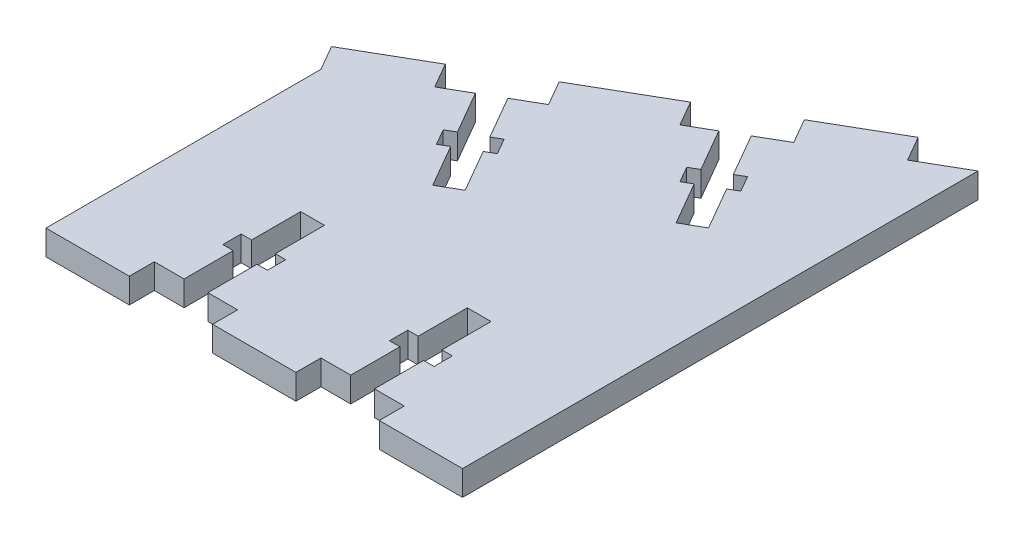
SolidWorks part; units mm, degrees
ref_plane "Front Plane" through (0, 0, 0) normal (0, 0, 1) x (1, 0, 0)
ref_plane "Top Plane" through (0, 0, 0) normal (0, 1, 0) x (1, 0, 0)
ref_plane "Right Plane" through (0, 0, 0) normal (1, 0, 0) x (0, 0, -1)
sketch "Sketch1" plane through (0, 0, 0) normal (0, 1, 0) x (1, 0, 0)
  line L0 (0, 0) -> (50, 0)
  line L1 (50, 0) -> (50, 28.8675)
  line L2 (50, 28.8675) -> (0, 0)
  line L3 (0, 0) -> (-1.7321, 3)
  line L4 (0, 0) -> (50, 0)
  line L5 (0, 0) -> (0, -30)
  line L6 (0, -30) -> (50, -30)
  line L7 (50, 0) -> (50, -30)
  line L8 (0, -30) -> (10, -30)
  line L9 (0, -30) -> (0, -33)
  line L10 (0, -33) -> (10, -33)
  line L11 (10, -30) -> (10, -33)
  line L12 (20, -30) -> (30, -30)
  line L13 (20, -30) -> (20, -33)
  line L14 (20, -33) -> (30, -33)
  line L15 (30, -30) -> (30, -33)
  line L16 (40, -30) -> (50, -30)
  line L17 (40, -30) -> (40, -33)
  line L18 (40, -33) -> (50, -33)
  line L19 (50, -30) -> (50, -33)
  line L20 (-1.7321, 3) -> (6.9282, 8)
  line L21 (6.9282, 8) -> (8.6603, 5)
  line L22 (17.3205, 10) -> (15.5885, 13)
  line L23 (15.5885, 13) -> (25.5885, 18.7735)
  line L24 (25.5885, 18.7735) -> (27.3205, 15.7735)
  line L25 (27.3205, 15.7735) -> (17.3205, 10)
  line L26 (8.6603, 5) -> (0, 0)
  line L27 (35.9808, 20.7735) -> (34.2487, 23.7735)
  line L28 (34.2487, 23.7735) -> (42.909, 28.7735)
  line L29 (42.909, 28.7735) -> (44.641, 25.7735)
  dimension "D1" = 0
  dimension "D2" = 30
  dimension "D3" = 10
  dimension "D4" = 10
  dimension "D5" = 10
  dimension "D6" = 10
  dimension "D7" = 3
  dimension "D8" = 3
  dimension "D9" = 3
  dimension "D10" = 30
  dimension "D11" = 3
  dimension "D12" = 3
  dimension "D13" = 3
  dimension "D14" = 10
  dimension "D15" = 10
  dimension "D16" = 10
  dimension "D17" = 10
  dimension "D18" = 10
extrude "Boss-Extrude1" add sketch "Sketch1" along normal blind 3 contours L1 L2 L0 | L21 L20 L3 L2 | L7 L0 L5 L6 | L11 L6 L9 L10 | L15 L6 L13 L14 | L19 L6 L17 L18 | L24 L23 L22 L2 | L29 L28 L27 L2
sketch "Sketch2" plane through (0, 3, 0) normal (0, 1, 0) x (1, 0, 0)
  line L0 (12.9904, 7.5) -> (19.9904, -4.6244)
  line L1 (17.3205, 10) -> (8.6603, 5) construction
  line L2 (18.7563, -5.3369) -> (21.2245, -3.9119)
  line L3 (18.807, 2.7753) -> (14.1738, 0.1003)
  line L4 (18.7563, -5.3369) -> (11.7563, 6.7875)
  line L5 (11.7563, 6.7875) -> (14.2245, 8.2125)
  line L6 (14.2245, 8.2125) -> (21.2245, -3.9119)
  line L7 (13.6238, 1.053) -> (14.7238, -0.8523)
  line L8 (14.7238, -0.8523) -> (19.357, 1.8227)
  line L9 (19.357, 1.8227) -> (18.257, 3.728)
  line L10 (18.257, 3.728) -> (13.6238, 1.053)
  line L11 (10, -30) -> (10, -33) construction
  line L12 (31.4808, 18.2456) -> (38.5112, 6.0686)
  line L13 (35, -16) -> (35, -30)
  line L14 (37.2771, 5.3561) -> (39.7453, 6.7811)
  line L15 (37.3126, 13.4946) -> (32.6794, 10.8196)
  line L16 (37.2771, 5.3561) -> (30.2771, 17.4805)
  line L17 (30.2771, 17.4805) -> (32.7453, 18.9055)
  line L18 (32.7453, 18.9055) -> (39.7453, 6.7811)
  line L19 (32.1294, 11.7723) -> (33.2294, 9.867)
  line L20 (33.2294, 9.867) -> (37.8626, 12.542)
  line L21 (37.8626, 12.542) -> (36.7626, 14.4473)
  line L22 (36.7626, 14.4473) -> (32.1294, 11.7723)
  line L23 (35.9808, 20.7735) -> (27.3205, 15.7735) construction
  line L24 (15, -16) -> (15, -30)
  line L25 (13.575, -30) -> (16.425, -30)
  line L26 (17.675, -23) -> (12.325, -23)
  line L27 (13.575, -30) -> (13.575, -16)
  line L28 (13.575, -16) -> (16.425, -16)
  line L29 (16.425, -16) -> (16.425, -30)
  line L30 (12.325, -21.9) -> (12.325, -24.1)
  line L31 (12.325, -24.1) -> (17.675, -24.1)
  line L32 (17.675, -24.1) -> (17.675, -21.9)
  line L33 (17.675, -21.9) -> (12.325, -21.9)
  line L35 (33.575, -30) -> (36.425, -30)
  line L36 (37.675, -23) -> (32.325, -23)
  line L37 (33.575, -30) -> (33.575, -16)
  line L38 (33.575, -16) -> (36.425, -16)
  line L39 (36.425, -16) -> (36.425, -30)
  line L40 (32.325, -21.9) -> (32.325, -24.1)
  line L41 (32.325, -24.1) -> (37.675, -24.1)
  line L42 (37.675, -24.1) -> (37.675, -21.9)
  line L43 (37.675, -21.9) -> (32.325, -21.9)
  line L44 (30, -30) -> (40, -30) construction
  line L45 (30, -30) -> (30, -33) construction
  line L46 (10, -30) -> (20, -30) construction
  point P7 (19.9904, -4.6244)
  point P10 (16.4904, 1.4378)
  point P15 (14.1738, 0.1003)
  point P22 (38.5112, 6.0686)
  point P25 (34.996, 12.1571)
  point P30 (32.6794, 10.8196)
  point P39 (15, -30)
  point P42 (15, -23)
  point P47 (12.325, -23)
  point P49 (0, 0)
  point P57 (35, -30)
  point P60 (35, -23)
  point P65 (32.325, -23)
  point P71 (0, 0)
  line M26 (35.9808, 20.7735) -> (27.3205, 15.7735)
  line M30 (17.3205, 10) -> (8.6603, 5)
  dimension "D1" = 0
  dimension "D2" = 5
  dimension "D3" = 0
  dimension "D4" = 5
  dimension "D5" = 0
extrude "Cut-Extrude1" cut sketch "Sketch2" against normal through all contours L8 L0 L2 L6 | L8 L4 L2 L0 | L10 L6 L0 M30 | L10 L0 L4 M30 | L0 L10 L4 L3 | L4 L10 L7 L3 | L7 L8 L4 L3 | L4 L8 L0 L3 | L8 L9 L3 L6 | L9 L10 L6 L3 | L6 L10 L0 L3 | L0 L8 L6 L3 | L22 L18 L12 M26 | L22 L12 L16 M26 | L16 L22 L19 L15 | L12 L22 L16 L15 | L18 L22 L12 L15 | L21 L22 L18 L15 | L20 L21 L15 L18 | L12 L20 L18 L15 | L16 L20 L12 L15 | L19 L20 L16 L15 | L20 L16 L14 L12 | L20 L12 L14 L18 | L33 L24 L28 L27 | L33 L29 L28 L24 | L24 L33 L27 L26 | L27 L33 L30 L26 | L39 L35 L37 L38 | L42 L43 L40 L41
